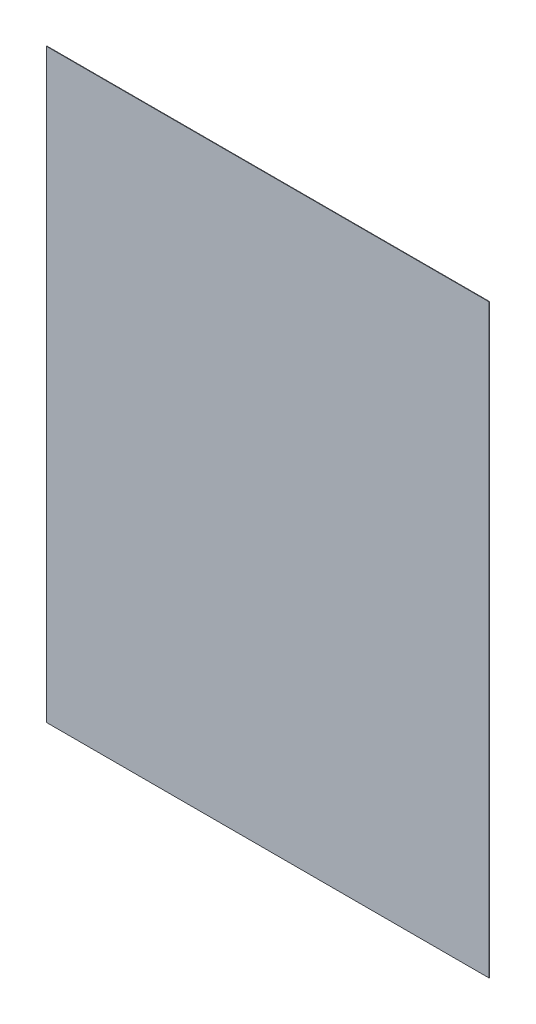
SolidWorks part; units mm, degrees
ref_plane "Front Plane" through (0, 0, 0) normal (0, 0, 1) x (1, 0, 0)
ref_plane "Top Plane" through (0, 0, 0) normal (0, 1, 0) x (1, 0, 0)
ref_plane "Right Plane" through (0, 0, 0) normal (1, 0, 0) x (0, 0, -1)
other "Configuration Table"
sketch "Sketch1" plane through (0, 0, 0) normal (0, 0, 1) x (1, 0, 0)
  line L1 (1.5, 120) -> (1398.5, 120)
  line L2 (1.5, 120) -> (1.5, 1968.5)
  line L3 (1.5, 1968.5) -> (1398.5, 1968.5)
  line L4 (1398.5, 120) -> (1398.5, 1968.5)
extrude "STORE_dis_arka_1" add sketch "Sketch1" against normal blind 1.5 from offset 818.5 separate body
